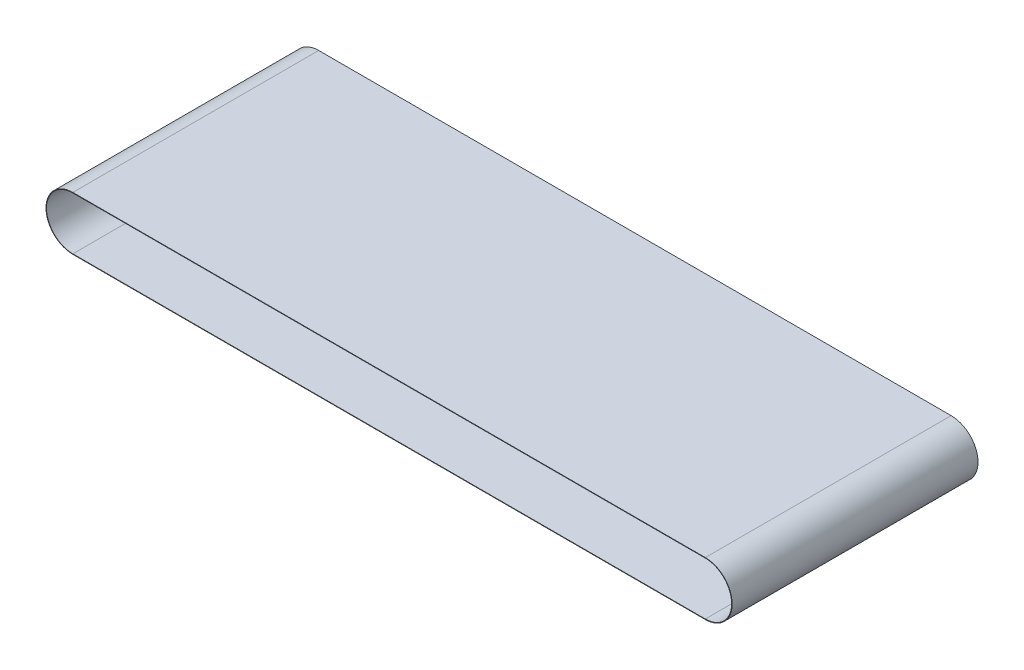
SolidWorks part; units mm, degrees
ref_plane "Front" through (0, 0, 0) normal (0, 0, 1) x (1, 0, 0)
ref_plane "Top" through (0, 0, 0) normal (0, 1, 0) x (1, 0, 0)
ref_plane "Right" through (0, 0, 0) normal (1, 0, 0) x (0, 0, -1)
sketch "草图2" plane through (0, 0, 0) normal (0, 0, 1) x (1, 0, 0)
  line L0 (0, 0) -> (1, 0) construction
  line L1 (0, 0) -> (0, 1) construction
  line L2 (0, 165) -> (3923.2761, 165)
  line L3 (3923.2761, -165) -> (0, -165)
  arc A0 (0, -165) -> (0, 165) centre (0, 0) cw
  arc A1 (3923.2761, 165) -> (3923.2761, -165) centre (3923.2761, 0) cw
sketch "草图4" plane through (0, 0, 0) normal (1, 0, 0) x (0, 0, -1)
  line L0 (0, 165) -> (0, -165) construction
  line L1 (-762.5, 166.5) -> (762.5, 166.5)
  line L2 (-762.5, 166.5) -> (-762.5, 163.5)
  line L3 (-762.5, 163.5) -> (762.5, 163.5)
  line L4 (762.5, 166.5) -> (762.5, 163.5)
  line L5 (-762.5, 166.5) -> (762.5, 163.5) construction
  line L6 (-762.5, 163.5) -> (762.5, 166.5) construction
  point P0 (0, 165)
  dimension "D1" = 1525
  dimension "D2" = 3
sweep "扫描1" add profiles "草图4" path "草图2"
